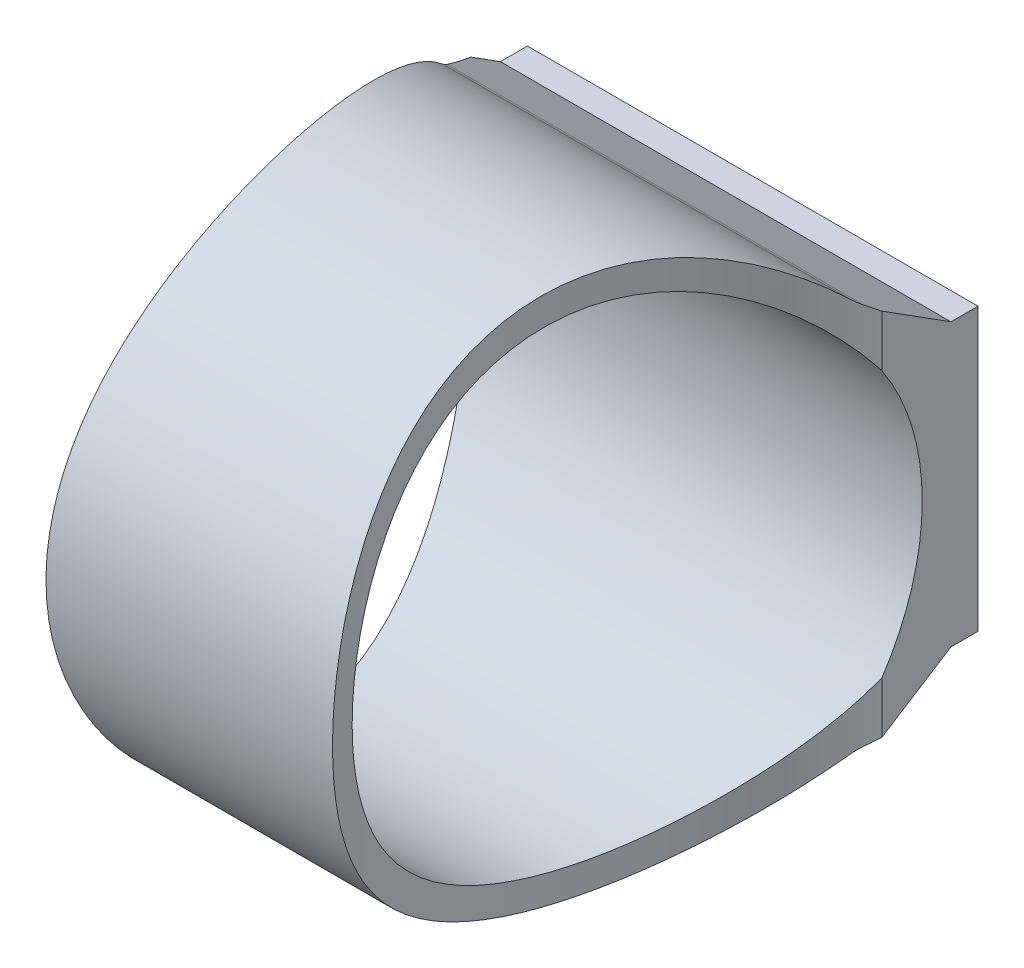
SolidWorks part; units mm, degrees
ref_plane "Front Plane" through (0, 0, 0) normal (0, 0, 1) x (1, 0, 0)
ref_plane "Top Plane" through (0, 0, 0) normal (0, 1, 0) x (1, 0, 0)
ref_plane "Right Plane" through (0, 0, 0) normal (1, 0, 0) x (0, 0, -1)
sketch "Sketch1" plane through (0, 0, 0) normal (1, 0, 0) x (0, 0, -1)
  line L0 (0, 0) -> (60.325, 0) construction
  line L1 (60.325, 0) -> (63.5, 0) construction
  line L2 (60.452, 31.75) -> (41.5828, 43.7033)
  line L3 (66.548, -31.75) -> (60.452, -31.75)
  line L4 (66.548, -31.75) -> (66.548, 31.75)
  line L5 (66.548, 31.75) -> (60.452, 31.75)
  line L7 (66.548, -31.75) -> (60.452, 31.75) construction
  line L8 (66.548, 31.75) -> (60.452, -31.75) construction
  line L9 (60.452, -31.75) -> (41.5828, -43.7033)
  circle A0 centre (0, 0) radius 60.325
  circle A1 centre (0, 0) radius 53.975
  dimension "D1" = 107.95
  dimension "D2" = 6.35
  dimension "D3" = 3.175
  dimension "D4" = 6.096
  dimension "D5" = 63.5
extrude "Boss-Extrude1" add sketch "Sketch1" along normal blind 101.6 contours A0 L9 L3 L4 L5 L2 | A0 A1
fillet "Fillet3" radius 12.7 2 edges at (50.8, -43.7033, -41.5828) (50.8, 43.7033, -41.5828)
sketch "Sketch3" plane through (0, 0, 0) normal (0, 1, 0) x (1, 0, 0)
  line L0 (0, 0) -> (110.5093, 0) construction
  line L12 (-10.1575, 69.3714) -> (-19.9455, 96.449)
  line L13 (-19.9455, 96.449) -> (-19.9455, -173.7689)
  line L14 (-19.9455, -173.7689) -> (157.6763, -157.239)
  line L15 (157.6763, -157.239) -> (148.2973, 47.8949)
  line L16 (148.2973, 47.8949) -> (143.4762, 77.1076)
  line L18 (12.2531, -82.1445) -> (82.9377, -60.325)
  line L19 (0, -60.325) -> (101.6, -60.325) construction
  arc A0 (143.4762, 77.1076) -> (82.9377, -60.325) centre (188.6337, -24.8339) ccw
  arc A1 (12.2531, -82.1445) -> (-10.1575, 69.3714) centre (-141.7933, -27.5141) ccw
  point P14 (124.0327, 45.2551)
  point P15 (81.092, -59.9729)
  point P16 (37.5923, -47.3246)
  point P17 (116.9099, 62.5694)
  point P18 (143.4762, 77.1076)
  point P19 (-10.1575, 69.3714)
  point P20 (12.2531, -82.1445)
  point P21 (82.9377, -60.325)
extrude "Cut-Extrude2" cut sketch "Sketch3" against normal through all both and the other way through all
